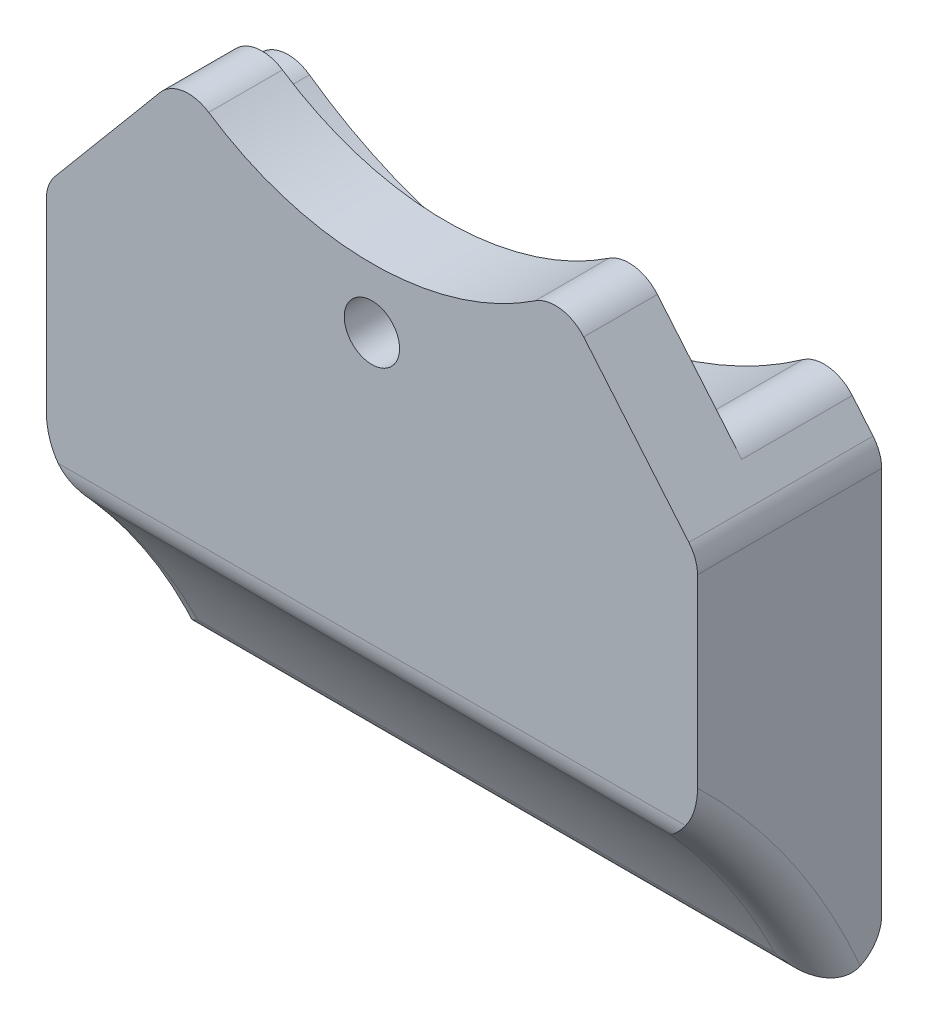
SolidWorks part; units mm, degrees
ref_plane "前视基准面" through (0, 0, 0) normal (0, 0, 1) x (1, 0, 0)
ref_plane "上视基准面" through (0, 0, 0) normal (0, 1, 0) x (1, 0, 0)
ref_plane "右视基准面" through (0, 0, 0) normal (1, 0, 0) x (0, 0, -1)
other "Configuration Table"
sketch "草图1" plane through (0, 0, 0) normal (0, 0, 1) x (1, 0, 0)
  line L0 (0, 0) -> (0, -23.1) construction
  line L1 (-10.2846, -12.2567) -> (-14.8484, -17.6956)
  line L2 (10.2846, -12.2567) -> (14.8484, -17.6956)
  circle A0 centre (0, -19.25) radius 1.5
  circle A1 centre (0, 0) radius 23.1
  circle A2 centre (0, 0) radius 16
  dimension "D1" = 3
  dimension "D3" = 46.2
  dimension "D4" = 32
  dimension "D2" = 19.25
  dimension "D5" = 80
extrude "凸台-拉伸1" add sketch "草图1" along normal blind 4 contours A2 L0 A0 A1 L2 | L0 A2 L1 A1 A0
sketch "草图3" plane through (0, 0, 4) normal (0, 0, 1) x (1, 0, 0)
  line L0 (-14.8484, -17.6956) -> (-17.6767, -21.0662)
  line L1 (14.8484, -17.6956) -> (17.6767, -21.0662)
  line L2 (-10.2846, -12.2567) -> (-14.8484, -17.6956)
  line L3 (14.8484, -17.6956) -> (10.2846, -12.2567)
  line L4 (-10.2846, -12.2567) -> (-14.8484, -17.6956)
  line L5 (14.8484, -17.6956) -> (10.2846, -12.2567)
  circle A0 centre (0, 0) radius 27.5
  arc A2 (-10.2846, -12.2567) -> (10.2846, -12.2567) centre (0, 0) ccw
  arc A3 (-14.8484, -17.6956) -> (14.8484, -17.6956) centre (0, 0) ccw
  arc A4 (-10.2846, -12.2567) -> (10.2846, -12.2567) centre (0, 0) ccw
  arc A5 (-14.8484, -17.6956) -> (14.8484, -17.6956) centre (0, 0) ccw
  arc M8 (-14.8484, -17.6956) -> (14.8484, -17.6956) centre (0, 0) ccw
  dimension "D2" = 55
  dimension "D1" = 0
extrude "凸台-拉伸2" add sketch "草图3" against normal blind 10 contours L0 A0 L1 M8
sketch "草图4" plane through (0, 0, 4) normal (0, 0, 1) x (1, 0, 0)
  line L0 (-17.6767, -21.0662) -> (-17.6767, -71.0662)
  line L1 (-17.6767, -71.0662) -> (17.6767, -71.0662)
  line L2 (-10.2846, -12.2567) -> (-17.6767, -21.0662)
  line L3 (17.6767, -21.0662) -> (10.2846, -12.2567)
  line L4 (-10.2846, -12.2567) -> (-17.6767, -21.0662)
  line L5 (17.6767, -21.0662) -> (10.2846, -12.2567)
  line L6 (17.6767, -71.0662) -> (17.6767, -21.0662)
  arc A2 (-10.2846, -12.2567) -> (10.2846, -12.2567) centre (0, 0) ccw
  arc A3 (-17.6767, -21.0662) -> (17.6767, -21.0662) centre (0, 0) ccw
  arc A4 (-10.2846, -12.2567) -> (10.2846, -12.2567) centre (0, 0) ccw
  arc A5 (-17.6767, -21.0662) -> (17.6767, -21.0662) centre (0, 0) ccw
  arc M9 (-17.6767, -21.0662) -> (17.6767, -21.0662) centre (0, 0) ccw
  dimension "D2" = 50
  dimension "D1" = 0
extrude "凸台-拉伸3" add sketch "草图4" against normal blind 10 contours L1 L6 L0 M9
sketch "草图7" plane through (17.6767, 0, 0) normal (1, 0, 0) x (0, 0, -1)
  line L3 (6, -71.0662) -> (6, -21.0662) construction
  line L6 (-4, -21.0662) -> (-4, -71.0662)
  line L7 (-4, -71.0662) -> (6, -71.0662)
  line L8 (6, -71.0662) -> (6, -21.0662)
  line L9 (6, -21.0662) -> (-4, -21.0662)
  line L10 (-4, -21.0662) -> (-4, -71.0662)
  line L11 (-4, -71.0662) -> (6, -71.0662)
  line L12 (6, -71.0662) -> (6, -21.0662)
  line L13 (6, -21.0662) -> (-4, -21.0662)
  arc A1 (-4, -34.6843) -> (6, -57.0622) centre (-31.9117, -60.5804) cw
  ellipse E0 centre (-23.8972, -55.0879) end of major axis (-23.8972, -83.5879) minor radius 28.4985 (-23.3887, -83.5834) -> (-24.4057, -26.5924) ccw construction
  point P0 (6, -56.5009)
  dimension "D1" = 0
extrude "切除-拉伸1" cut sketch "草图7" against normal through all
fillet "圆角1" radius 2 10 edges at (14.8484, -17.6956, -3) (-14.8484, -17.6956, -3) (-17.6767, -21.0662, -1) (10.2846, -12.2567, 2) (17.6767, -21.0662, -1) (-10.2846, -12.2567, 2) (0, -34.6843, 4) (0, -57.0622, -6) (-17.6767, -45.0466, -2.85) (17.6767, -45.0466, -2.85)
